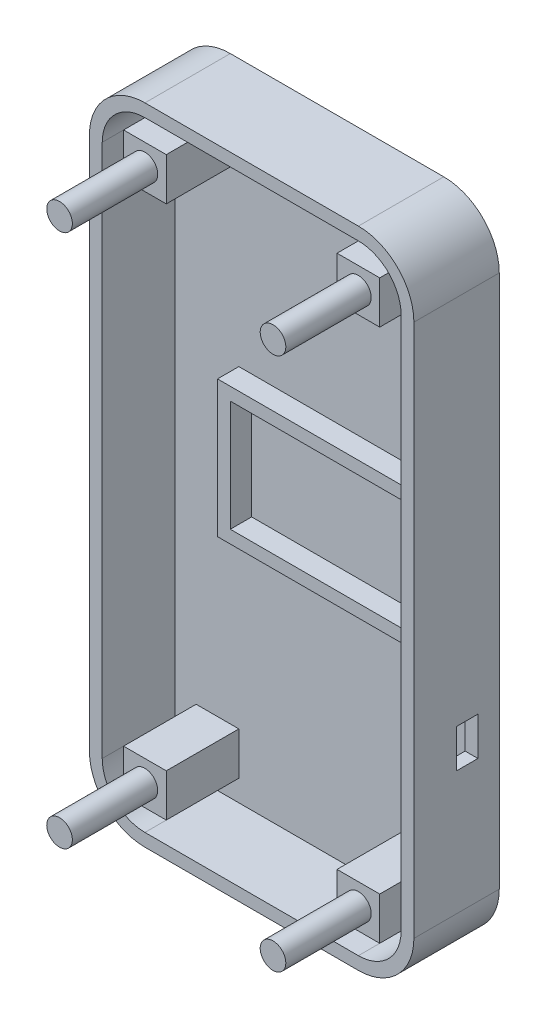
SolidWorks part; units mm, degrees
ref_plane "Front Plane" through (0, 0, 0) normal (0, 0, 1) x (1, 0, 0)
ref_plane "Top Plane" through (0, 0, 0) normal (0, 1, 0) x (1, 0, 0)
ref_plane "Right Plane" through (0, 0, 0) normal (1, 0, 0) x (0, 0, -1)
sketch "Sketch1" plane through (0, 0, 0) normal (0, 0, 1) x (1, 0, 0)
  line L1 (-25, 75.5) -> (25, 75.5)
  line L2 (-25, 72.5) -> (25, 72.5)
  line L3 (-35, 62.5) -> (-35, -62.5)
  line L4 (-25, -72.5) -> (25, -72.5)
  line L5 (35, 62.5) -> (35, -62.5)
  line L6 (-35, 72.5) -> (35, -72.5) construction
  line L7 (-35, -72.5) -> (35, 72.5) construction
  line L8 (38, 62.5) -> (38, -62.5)
  line L9 (-25, -75.5) -> (25, -75.5)
  line L10 (-38, 62.5) -> (-38, -62.5)
  arc A0 (-35, -62.5) -> (-25, -72.5) centre (-25, -62.5) ccw
  arc A1 (25, -72.5) -> (35, -62.5) centre (25, -62.5) ccw
  arc A2 (25, 72.5) -> (35, 62.5) centre (25, 62.5) cw
  arc A3 (-25, 72.5) -> (-35, 62.5) centre (-25, 62.5) ccw
  arc A4 (25, 75.5) -> (38, 62.5) centre (25, 62.5) cw
  arc A5 (25, -75.5) -> (38, -62.5) centre (25, -62.5) ccw
  arc A6 (-38, -62.5) -> (-25, -75.5) centre (-25, -62.5) ccw
  arc A7 (-25, 75.5) -> (-38, 62.5) centre (-25, 62.5) ccw
  point P2 (0, 0)
  dimension "D3" = 10
  dimension "D1" = 70
  dimension "D2" = 145
  dimension "D4" = 3
extrude "Boss-Extrude1" add sketch "Sketch1" along normal blind 20
sketch "Sketch3" plane through (0, 0, 0) normal (0, 0, -1) x (-1, 0, 0)
  line L1 (25, -75.5) -> (-25, -75.5)
  line L2 (38, -62.5) -> (38, 62.5)
  line L3 (25, 75.5) -> (-25, 75.5)
  line L4 (-38, -62.5) -> (-38, 62.5)
  line L5 (38, -75.5) -> (-38, 75.5) construction
  line L6 (38, 75.5) -> (-38, -75.5) construction
  line L11 (-25, 75.5) -> (25, 75.5) construction
  line L12 (-38, -62.5) -> (-38, 62.5) construction
  arc A0 (-25, -75.5) -> (-38, -62.5) centre (-25, -62.5) cw
  arc A1 (25, -75.5) -> (38, -62.5) centre (25, -62.5) ccw
  arc A2 (38, 62.5) -> (25, 75.5) centre (25, 62.5) ccw
  arc A3 (-25, 75.5) -> (-38, 62.5) centre (-25, 62.5) ccw
  arc A6 (-25, 75.5) -> (-38, 62.5) centre (-25, 62.5) ccw construction
  point P0 (0, 0)
extrude "Boss-Extrude2" add sketch "Sketch3" against normal blind 3
sketch "Sketch4" plane through (0, 0, 3) normal (0, 0, 1) x (1, 0, 0)
  line L0 (0, 0) -> (0, 36.7232) construction
  line L1 (0, 0) -> (29.5031, 0) construction
  line L2 (25, 72.5) -> (-25, 72.5) construction
  line L3 (-30, 67.5) -> (-20, 67.5)
  line L4 (-30, 67.5) -> (-30, 57.5)
  line L5 (-30, 57.5) -> (-20, 57.5)
  line L6 (-20, 67.5) -> (-20, 57.5)
  line L7 (-30, 67.5) -> (-20, 57.5) construction
  line L8 (-30, 57.5) -> (-20, 67.5) construction
  line L9 (-35, 62.5) -> (-35, -62.5) construction
  line L10 (30, 57.5) -> (20, 67.5) construction
  line L11 (30, 67.5) -> (20, 57.5) construction
  line L12 (20, 67.5) -> (20, 57.5)
  line L13 (30, 57.5) -> (20, 57.5)
  line L14 (30, 67.5) -> (30, 57.5)
  line L15 (30, 67.5) -> (20, 67.5)
  line L16 (30, -67.5) -> (20, -57.5) construction
  line L17 (30, -57.5) -> (20, -67.5) construction
  line L18 (30, -67.5) -> (20, -67.5)
  line L19 (30, -67.5) -> (30, -57.5)
  line L20 (30, -57.5) -> (20, -57.5)
  line L21 (20, -67.5) -> (20, -57.5)
  line L22 (-30, -67.5) -> (-20, -67.5)
  line L23 (-30, -57.5) -> (-20, -67.5) construction
  line L24 (-30, -67.5) -> (-20, -57.5) construction
  line L25 (-20, -67.5) -> (-20, -57.5)
  line L26 (-30, -57.5) -> (-20, -57.5)
  line L27 (-30, -67.5) -> (-30, -57.5)
  point P3 (-25, 62.5)
  point P17 (25, 62.5)
  point P22 (25, -62.5)
  point P27 (-25, -62.5)
  dimension "D1" = 10
  dimension "D2" = 10
  dimension "D3" = 5
  dimension "D4" = 5
extrude "Boss-Extrude3" add sketch "Sketch4" along normal blind 17
sketch "Sketch5" plane through (0, 0, 20) normal (0, 0, 1) x (1, 0, 0)
  line L0 (0, 75.5) -> (0, -75.5) construction
  line L1 (25, 75.5) -> (-25, 75.5) construction
  line L16 (-25, -75.5) -> (25, -75.5) construction
  line L17 (38, 0) -> (-38, 0) construction
  line L18 (38, -62.5) -> (38, 62.5) construction
  line L19 (-38, 62.5) -> (-38, -62.5) construction
  line L20 (-30, 67.5) -> (-30, 57.5) construction
  line L21 (-20, 67.5) -> (-30, 67.5) construction
  circle A4 centre (-25, 62.5) radius 3
  circle A5 centre (25, 62.5) radius 3
  circle A6 centre (25, -62.5) radius 3
  circle A7 centre (-25, -62.5) radius 3
  point P7 (27.95, 62.5)
  point P17 (0, 0)
  point P18 (-27.95, 62.5)
  point P21 (-30, 62.5)
  point P22 (0, 0)
  point P25 (-25, 67.5)
  point P27 (-27.95, -62.5)
  point P28 (27.95, -62.5)
  dimension "D1" = 6
extrude "Boss-Extrude4" add sketch "Sketch5" along normal blind 20
sketch "Sketch6" plane through (38, 0, 0) normal (1, 0, 0) x (0, 0, -1)
  line L0 (0, -62.5) -> (0, 62.5) construction
  line L1 (-10, -24.5) -> (-5, -24.5)
  line L2 (-10, -24.5) -> (-10, -33.5)
  line L3 (-10, -33.5) -> (-5, -33.5)
  line L4 (-5, -24.5) -> (-5, -33.5)
  line L5 (-10, -24.5) -> (-5, -33.5) construction
  line L6 (-10, -33.5) -> (-5, -24.5) construction
  line L7 (-20, 75.5) -> (0, 75.5) construction
  line L8 (-20, -53.5) -> (5.397, -53.5) construction
  line L9 (-20, -62.5) -> (-20, 62.5) construction
  line L10 (-10, -73.5) -> (-5, -82.5) construction
  line L11 (-10, -82.5) -> (-5, -73.5) construction
  line L12 (-5, -82.5) -> (-5, -73.5)
  line L13 (-10, -73.5) -> (-5, -73.5)
  line L14 (-10, -82.5) -> (-10, -73.5)
  line L15 (-10, -82.5) -> (-5, -82.5)
  point P0 (-7.5, -29)
  point P17 (-7.5, -78)
  dimension "D1" = 5
  dimension "D2" = 9
  dimension "D3" = 5
  dimension "D4" = 100
  dimension "D5" = 20
extrude "Cut-Extrude1" cut sketch "Sketch6" against normal blind 30
sketch "Sketch7" plane through (0, 0, 3) normal (0, 0, 1) x (1, 0, 0)
  line L0 (35, -62.5) -> (35, 62.5) construction
  line L1 (-17, 13) -> (35, 13)
  line L2 (-17, 13) -> (-17, -13)
  line L3 (-17, -13) -> (35, -13)
  line L4 (35, 13) -> (35, -13)
  line L5 (-17, 13) -> (35, -13) construction
  line L6 (-17, -13) -> (35, 13) construction
  line L7 (-20, 16) -> (38, 16)
  line L8 (38, 16) -> (38, -16)
  line L9 (-20, -16) -> (38, -16)
  line L10 (-20, 16) -> (-20, -16)
  point P0 (9, 0)
  dimension "D1" = 26
  dimension "D2" = 52
  dimension "D3" = 3
  dimension "0" = 0
extrude "Boss-Extrude5" add sketch "Sketch7" along normal blind 5
equation "\"length\"= 145"
equation "\"width\"= 70"
equation "\"D1@Sketch1\"=\"width\""
equation "\"D2@Sketch1\"=\"length\""
